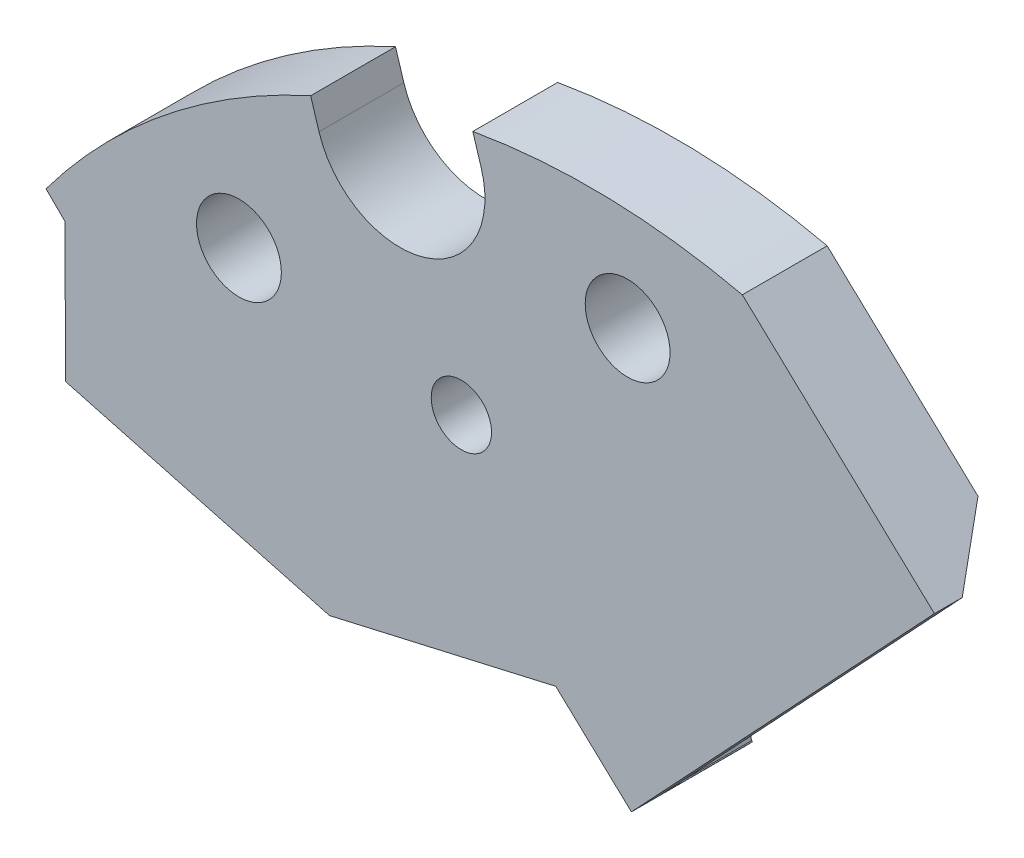
SolidWorks part; units mm, degrees
ref_plane "Piano frontale" through (0, 0, 0) normal (0, 0, 1) x (1, 0, 0)
ref_plane "Piano superiore" through (0, 0, 0) normal (0, 1, 0) x (1, 0, 0)
ref_plane "Piano destro" through (0, 0, 0) normal (1, 0, 0) x (0, 0, -1)
sketch "Schizzo1" plane through (0, 0, 0) normal (0, 0, 1) x (1, 0, 0)
  line L0 (0, 0) -> (-3.6477, 3.4197)
  line L1 (-3.6477, 3.4197) -> (-27.6477, -2.0803)
  line L2 (-27.6477, -2.0803) -> (-55.6477, 5.4197)
  line L3 (-55.6477, 5.4197) -> (-55.7149, 20.1021)
  line L4 (0, 0) -> (32.1452, 34.2882)
  line L5 (32.1452, 34.2882) -> (16.1452, 49.2882)
  line L6 (32.1452, 34.2882) -> (16.1452, 34.2882) construction
  line L7 (16.1452, 34.2882) -> (16.1452, 49.2882) construction
  line L8 (-3.6477, 3.4197) -> (-27.6477, 3.4197) construction
  line L9 (-27.6477, 3.4197) -> (-27.6477, -2.0803) construction
  line L10 (-55.6477, 5.4197) -> (-27.6477, 5.4197) construction
  line L11 (-27.6477, 5.4197) -> (-27.6477, 3.4197) construction
  line L12 (-55.6477, 5.4197) -> (-51.7149, 20.1021) construction
  line L13 (-51.7149, 20.1021) -> (-55.7149, 20.1021) construction
  line L14 (-55.7149, 20.1021) -> (-57.7241, 22.093)
  line L15 (-55.7149, 20.1021) -> (-55.7241, 22.1021) construction
  line L16 (-55.7241, 22.1021) -> (-57.7241, 22.093) construction
  line L17 (-29.6477, 44.682) -> (-29.6477, 5.4197) construction
  line L18 (-12.4477, 50.0001) -> (-12.4477, 3.4197) construction
  line L19 (-29.6477, 44.682) -> (-12.4477, 50.0001) construction
  line L20 (-21.9334, 50.2056) -> (-20.162, 44.4766) construction
  line L21 (-13.3334, 52.8646) -> (-11.562, 47.1356)
  line L22 (-30.5334, 47.5465) -> (-28.762, 41.8175)
  arc A0 (16.1452, 49.2882) -> (-57.7241, 22.093) centre (0.0895, -21.0217) ccw
  arc A1 (-13.3334, 52.8646) -> (-30.5334, 47.5465) centre (-21.9334, 50.2056) ccw
  arc A2 (-28.762, 41.8175) -> (-11.562, 47.1356) centre (-20.162, 44.4766) ccw
  point P21 (-21.0477, 47.3411)
  point P26 (-17.503, 35.8766)
  dimension "D15" = 26
  dimension "D18" = 72.1199
  dimension "D1" = 90
  dimension "D2" = 90
  dimension "D3" = 5
  dimension "D4" = 16
  dimension "D5" = 15
  dimension "D6" = 24
  dimension "D7" = 5.5
  dimension "D8" = 28
  dimension "D9" = 2
  dimension "D10" = 47
  dimension "D11" = 15.2
  dimension "D12" = 4
  dimension "D13" = 2
  dimension "D14" = 2
  dimension "D16" = 17.2
  dimension "D17" = 12
extrude "Estrusione-Estrusione1" add sketch "Schizzo1" along normal blind 9 contours A2 L22 A0 L14 L3 L2 L1 L0 L4 L5 L21
sketch "Schizzo2" plane through (0, 0, 9) normal (0, 0, 1) x (1, 0, 0)
  line L0 (32.1452, 34.2882) -> (36.5225, 30.1846) construction
  line L1 (0, 0) -> (4.3772, -4.1036) construction
  line L2 (36.5225, 30.1846) -> (4.3772, -4.1036)
  dimension "D1" = 6
  dimension "D2" = 6
extrude "Estrusione-Sottile1" add sketch "Schizzo2" against normal blind 3 separate body thin
loft "Loft1" add section face at (20.4134, 13.0747, 7.5) section face at (16.0726, 17.1441, 4.5)
sketch "Schizzo3" plane through (0, 0, 0) normal (0, 0, -1) x (-1, 0, 0)
  line L0 (0, 0) -> (3.6477, 3.4197)
  line L1 (3.6477, 3.4197) -> (14.2435, 0.9915)
  line L2 (3.6477, 3.4197) -> (27.6477, -2.0803) construction
  line L3 (14.2435, 0.9915) -> (15.137, 4.8904)
  line L4 (15.137, 4.8904) -> (2.4655, 7.7943)
  line L5 (2.4655, 7.7943) -> (-2.7358, 2.9181)
  line L6 (0, 0) -> (-32.1452, 34.2882) construction
  line L7 (-2.7358, 2.9181) -> (0, 0)
  dimension "D1" = 4
  dimension "D2" = 4
  dimension "D3" = 13
extrude "Estrusione-Estrusione2" add sketch "Schizzo3" along normal blind 3.5
sketch "Schizzo4" plane through (4.3772, -4.1036, 0) normal (0.7295, -0.6839, 0) x (0, 0, -1)
  line L0 (3.5, 0) -> (-6, 0)
  line L1 (-6, 0) -> (-6, 0.5)
  line L2 (-6, 47) -> (-6, 0) construction
  line L3 (-6, 0.5) -> (3.5, 0.5)
  line L4 (3.5, 4) -> (3.5, 0) construction
  line L5 (3.5, 0.5) -> (3.5, 0)
  dimension "D1" = 0.5
extrude "Estrusione-Estrusione3" add sketch "Schizzo4" against normal blind 0.1
loft "Loft3" add section face at (4.4753, -3.8529, 1.2248) section face at (1.3679, 1.4591, -1.75)
sketch "Schizzo5" plane through (0, 0, 0) normal (0, 0, -1) x (-1, 0, 0)
  line L0 (14.2435, 0.9915) -> (27.6477, -2.0803)
  line L1 (27.6477, -2.0803) -> (55.6477, 5.4197)
  line L2 (55.6477, 5.4197) -> (55.6667, 9.5658)
  line L3 (55.6477, 5.4197) -> (55.7149, 20.1021) construction
  line L4 (55.6667, 9.5658) -> (27.6866, 2.0712)
  line L5 (27.6866, 2.0712) -> (15.137, 4.8904)
  line L17 (15.137, 4.8904) -> (14.2435, 0.9915)
  line L18 (14.2435, 0.9915) -> (27.6477, -2.0803)
  line L19 (27.6477, -2.0803) -> (55.6477, 5.4197)
  line L20 (55.6477, 5.4197) -> (55.7149, 20.1021)
  line L21 (55.7149, 20.1021) -> (57.7241, 22.093)
  line L22 (29.6477, 44.682) -> (28.762, 41.8175)
  line L23 (11.562, 47.1356) -> (12.4477, 50.0001)
  line L24 (-16.1452, 49.2882) -> (-32.1452, 34.2882)
  line L25 (-32.1452, 34.2882) -> (-2.7358, 2.9181)
  line L26 (-2.7358, 2.9181) -> (2.4655, 7.7943)
  line L27 (2.4655, 7.7943) -> (15.137, 4.8904)
  line L28 (15.137, 4.8904) -> (14.2435, 0.9915)
  arc A3 (57.7241, 22.093) -> (29.6477, 44.682) centre (-0.0895, -21.0217) ccw
  arc A4 (11.562, 47.1356) -> (28.762, 41.8175) centre (20.162, 44.4766) ccw
  arc A5 (12.4477, 50.0001) -> (-16.1452, 49.2882) centre (-0.0895, -21.0217) ccw
  point P4 (27.6477, 2.0712)
  dimension "D1" = 4
  dimension "D2" = 0.246
  dimension "D3" = 0
extrude "Estrusione-Estrusione4" add sketch "Schizzo5" along normal blind 24
sketch "Schizzo6" plane through (0, 0, 0) normal (0, 0, -1) x (-1, 0, 0)
  line L0 (55.6667, 9.5658) -> (42.8196, 6.1246) construction
  line L1 (55.6667, 9.5658) -> (27.6866, 2.0712) construction
  line L2 (42.8196, 6.1246) -> (37.2567, 26.8925) construction
  line L3 (-3.976, 40.1359) -> (13.6596, 23.3458) construction
  circle A0 centre (-3.976, 40.1359) radius 4.5
  circle A1 centre (13.6596, 23.3458) radius 3.2
  arc A2 (11.562, 47.1356) -> (28.762, 41.8175) centre (20.162, 44.4766) ccw construction
  circle A3 centre (37.2567, 26.8925) radius 4.5
  point P5 (17.503, 35.8766)
  dimension "D3" = 12.5307
  dimension "D1" = 9
  dimension "D4" = 6.4
  dimension "D7" = 9
  dimension "D2" = 24.35
  dimension "D5" = 13.3
  dimension "D6" = 21.5
extrude "Taglio-Estrusione1" cut sketch "Schizzo6" against normal through all
